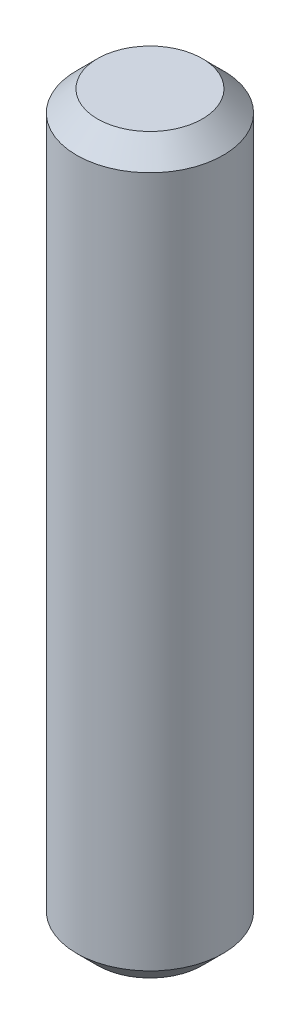
SolidWorks part; units mm, degrees
ref_plane "Front Plane" through (0, 0, 0) normal (0, 0, 1) x (1, 0, 0)
ref_plane "Top Plane" through (0, 0, 0) normal (0, 1, 0) x (1, 0, 0)
ref_plane "Right Plane" through (0, 0, 0) normal (1, 0, 0) x (0, 0, -1)
sketch "Sketch1" plane through (0, 0, 0) normal (0, 1, 0) x (1, 0, 0)
  circle A0 centre (0, 0) radius 7
  dimension "D1" = 14
extrude "Boss-Extrude1" add sketch "Sketch1" along normal blind 70
chamfer "Chamfer1" distance 2 angle 45 2 edges at (0, 0, 7) (0, 70, 7)
